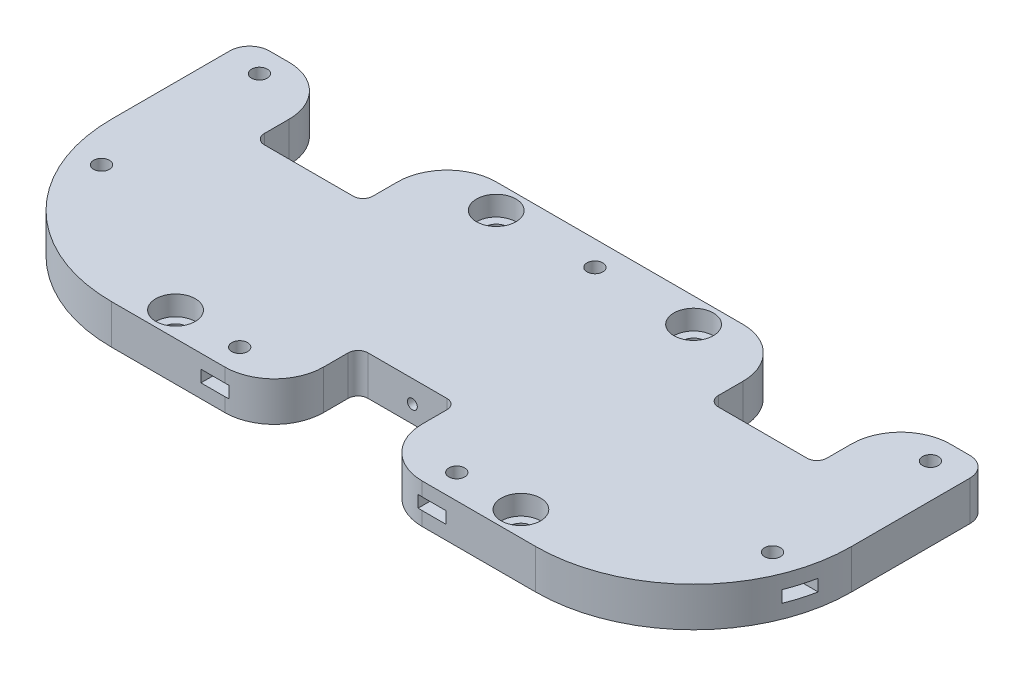
SolidWorks part; units mm, degrees
ref_plane "Front Plane" through (0, 0, 0) normal (0, 0, 1) x (1, 0, 0)
ref_plane "Top Plane" through (0, 0, 0) normal (0, 1, 0) x (1, 0, 0)
ref_plane "Right Plane" through (0, 0, 0) normal (1, 0, 0) x (0, 0, -1)
sketch "Sketch1" plane through (0, 0, 0) normal (0, 1, 0) x (1, 0, 0)
  line L1 (75, -13) -> (-75, -13)
  line L2 (75, -13) -> (75, 13)
  line L3 (75, 13) -> (-75, 13)
  line L4 (-75, -13) -> (-75, 13)
  line L5 (75, -13) -> (-75, 13) construction
  line L6 (75, 13) -> (-75, -13) construction
  point P0 (0, 0)
  dimension "D1" = 26
  dimension "D2" = 150
extrude "Boss-Extrude1" add sketch "Sketch1" along normal blind 8
sketch "Sketch2" plane through (0, 0, -13) normal (0, 0, -1) x (-1, 0, 0)
  line L0 (-75, 0) -> (75, 0) construction
  circle A0 centre (47.4, 3.5) radius 1
  circle A1 centre (-49.4, 3.5) radius 1
  dimension "D1" = 2
  dimension "D2" = 3.5
  dimension "D3" = 47.4
  dimension "D4" = 49.4
extrude "Cut-Extrude1" cut sketch "Sketch2" against normal blind 10
sketch "Sketch3" plane through (0, 0, 13) normal (0, 0, 1) x (1, 0, 0)
  line L0 (-75, 0) -> (75, 0) construction
  circle A0 centre (1, 3.5) radius 1
  dimension "D2" = 2
  dimension "D1" = 1
  dimension "D3" = 3.5
extrude "Cut-Extrude2" cut sketch "Sketch3" against normal blind 10 contours A0
sketch "Sketch4" plane through (0, 0, 0) normal (0, 1, 0) x (1, 0, 0)
  line L0 (-75, 13) -> (-75, -13) construction
  line L1 (-75, 0) -> (-10, 0)
  line L2 (-75, 0) -> (-75, -30)
  line L3 (-75, -30) -> (-10, -30)
  line L4 (-10, 0) -> (-10, -30)
  line L6 (10, 0) -> (75, 0)
  line L7 (10, 0) -> (10, -30)
  line L8 (10, -30) -> (75, -30)
  line L9 (75, 0) -> (75, -30)
  dimension "D1" = 20
  dimension "D2" = 30
extrude "Boss-Extrude2" add sketch "Sketch4" along normal up to surface (8 mm away) up to face at (0, 8, 0)
fillet "Fillet1" radius 32 2 edges at (75, 4, 30) (-75, 4, 30)
sketch "Sketch5" plane through (0, 0, 0) normal (0, 1, 0) x (1, 0, 0)
  line L1 (-35, 0) -> (35, 0)
  line L2 (-35, 0) -> (-35, 30)
  line L3 (-35, 30) -> (35, 30)
  line L4 (35, 0) -> (35, 30)
  dimension "D1" = 70
  dimension "D2" = 30
extrude "Boss-Extrude3" add sketch "Sketch5" along normal up to surface (8 mm away) up to face at (0, 8, 12.9255)
sketch "Sketch6" plane through (0, 0, 0) normal (0, -1, 0) x (1, 0, 0)
  point P0 (35, 25)
  point P1 (-35, 25)
  point P4 (-20, -25)
  point P6 (20, -25)
hole_wizard "CBORE for M4 SHCS1" positions "Sketch9" profile "Sketch8" counterbore size "M4" standard "ANSI Metric" end condition through all
sketch "Sketch9" plane through (0, 8, 0) normal (0, 1, 0) x (1, 0, 0)
  point P0 (-20, 25)
  point P3 (20, 25)
  point P6 (35, -25)
  point P9 (-35, -25)
sketch "Sketch8" plane through (-20, 8, -25) normal (1, 0, 0) x (0, 0, 1)
  line L0 (0, 0) -> (0, 8)
  line L1 (0, 8) -> (2.25, 8)
  line L3 (2.25, 8) -> (2.25, 4)
  line L4 (2.25, 4) -> (4, 4)
  line L5 (4, 4) -> (4, 0)
  line L7 (4, 0) -> (0, 0)
  line L11 (0, -6.35) -> (0, 107.95) construction
  dimension "Thru Hole Dia." = 4.5
  dimension "Thru Hole Depth" = 8
  dimension "C'Bore Dia." = 8
  dimension "C'Bore Depth" = 4
sketch "Sketch10" plane through (0, 8, 0) normal (0, 1, 0) x (1, 0, 0)
  line L0 (35, 30) -> (-35, 30) construction
  line L1 (-75, 13) -> (-57, 13)
  line L2 (-75, 13) -> (-75, 30)
  line L3 (-75, 30) -> (-57, 30)
  line L4 (-57, 13) -> (-57, 30)
  line L5 (75, 13) -> (57, 13)
  line L6 (75, 13) -> (75, 30)
  line L7 (75, 30) -> (57, 30)
  line L8 (57, 13) -> (57, 30)
  dimension "D1" = 18
extrude "Boss-Extrude4" add sketch "Sketch10" against normal up to surface (8 mm away) up to face at (-20, 0, -22.75)
fillet "Fillet2" radius 10 6 edges at (35, 4, -30) (-35, 4, -30) (10, 4, 30) (-10, 4, 30) (57, 4, -30) (-57, 4, -30)
fillet "Fillet3" radius 2 6 edges at (35, 4, -13) (10, 4, 13) (-10, 4, 13) (-35, 4, -13) (-57, 4, -13) (57, 4, -13)
fillet "Fillet4" radius 4 2 edges at (75, 4, -30) (-75, 4, -30)
sketch "Sketch11" plane through (0, 8, 0) normal (0, 1, 0) x (1, 0, 0)
  circle A0 centre (-68, 25) radius 1.6
  circle A1 centre (-68, -7) radius 1.6
  circle A4 centre (0, 25) radius 1.6
  circle A5 centre (-22, -25) radius 1.6
  circle A6 centre (22, -25) radius 1.6
  circle A9 centre (68, -7) radius 1.6
  circle A10 centre (68, 25) radius 1.6
  dimension "D1" = 3.2
extrude "Cut-Extrude3" cut sketch "Sketch11" against normal through all
sketch "Sketch12" plane through (0, 8, 0) normal (0, 1, 0) x (1, 0, 0)
  point P0 (-68, 25)
  point P1 (-68, -7)
  point P5 (-22, -25)
  point P9 (0, 25)
  point P11 (22, -25)
  point P15 (68, -7)
  point P17 (68, 25)
sketch "Sketch14" plane through (0, 8, 0) normal (0, 1, 0) x (1, 0, 0)
  line L0 (19.15, -26.6454) -> (19.15, -29.9638)
  line L1 (19.15, -29.9638) -> (19.15, -31.0884)
  line L2 (19.15, -31.0884) -> (24.85, -31.0884)
  line L3 (-70.85, 26.6454) -> (-70.85, 23.3546)
  line L4 (-70.85, 23.3546) -> (-68, 21.7091)
  line L5 (-68, 21.7091) -> (-65.15, 23.3546)
  line L6 (-65.15, 23.3546) -> (-65.15, 26.6454)
  line L7 (-66.3546, -9.85) -> (-64.7091, -7)
  line L8 (-64.7091, -7) -> (-66.3546, -4.15)
  line L9 (-66.3546, -4.15) -> (-69.6454, -4.15)
  line L10 (24.85, -31.0884) -> (24.85, -30)
  line L12 (-69.6454, -9.85) -> (-66.3546, -9.85)
  line L13 (24.85, -26.6454) -> (24.85, -30)
  line L14 (20, -30) -> (43, -30) construction
  line L17 (69.6454, -4.15) -> (74.8554, -4.15)
  line L19 (-19.15, -26.6454) -> (-19.15, -23.3546)
  line L20 (-19.15, -23.3546) -> (-22, -21.7091)
  line L21 (-22, -21.7091) -> (-24.85, -23.3546)
  line L22 (-24.85, -23.3546) -> (-24.85, -26.6454)
  line L25 (69.6454, -9.85) -> (74.8554, -9.85)
  line L26 (74.8554, -4.15) -> (74.8554, -9.85)
  line L28 (65.15, 26.6454) -> (65.15, 32.1621)
  line L29 (65.15, 32.1621) -> (70.85, 32.1621)
  line L30 (70.85, 26.6454) -> (70.85, 32.1621)
  line L33 (-2.85, 26.6454) -> (-2.85, 23.3546)
  line L34 (-2.85, 23.3546) -> (0, 21.7091)
  line L35 (0, 21.7091) -> (2.85, 23.3546)
  line L36 (2.85, 23.3546) -> (2.85, 26.6454)
  line L38 (-2.85, 26.6454) -> (-2.85, 32.1621)
  line L39 (-2.85, 32.1621) -> (2.85, 32.1621)
  line L40 (2.85, 26.6454) -> (2.85, 32.1621)
  line L42 (-70.85, 26.6454) -> (-70.85, 32.1621)
  line L43 (24.85, -26.6454) -> (24.85, -23.3546)
  line L44 (24.85, -23.3546) -> (22, -21.7091)
  line L45 (22, -21.7091) -> (19.15, -23.3546)
  line L46 (19.15, -23.3546) -> (19.15, -26.6454)
  line L49 (-70.85, 32.1621) -> (-65.15, 32.1621)
  line L50 (-65.15, 26.6454) -> (-65.15, 32.1621)
  line L51 (-69.6454, -4.15) -> (-77.0635, -4.15)
  line L53 (-69.6454, -9.85) -> (-77.0635, -9.85)
  line L54 (-77.0635, -4.15) -> (-77.0635, -9.85)
  line L55 (66.3546, -4.15) -> (64.7091, -7)
  line L56 (64.7091, -7) -> (66.3546, -9.85)
  line L57 (66.3546, -9.85) -> (69.6454, -9.85)
  line L60 (69.6454, -4.15) -> (66.3546, -4.15)
  line L61 (68, 21.7091) -> (70.85, 23.3546)
  line L62 (70.85, 23.3546) -> (70.85, 26.6454)
  line L65 (65.15, 26.6454) -> (65.15, 23.3546)
  line L66 (65.15, 23.3546) -> (68, 21.7091)
  line L68 (-24.85, -26.6454) -> (-24.85, -31.7239)
  line L69 (-24.85, -31.7239) -> (-19.15, -31.7239)
  line L70 (-19.15, -26.6454) -> (-19.15, -31.7239)
  line L71 (-66.575, 27.4682) -> (-68, 28.2909) [skipped]
  line L72 (-68, 28.2909) -> (-69.425, 27.4682) [skipped]
  line L73 (-70.4682, -5.575) -> (-71.2909, -7) [skipped]
  line L74 (-70.4682, -8.425) -> (-69.6454, -9.85) [skipped]
  line L75 (-22, -28.2909) -> (-20.575, -27.4682) [skipped]
  line L76 (-24.85, -26.6454) -> (-23.425, -27.4682) [skipped]
  line L77 (22, -28.2909) -> (23.425, -27.4682) [skipped]
  line L78 (19.15, -26.6454) -> (20.575, -27.4682) [skipped]
  line L79 (70.4682, -8.425) -> (71.2909, -7) [skipped]
  line L80 (70.4682, -5.575) -> (69.6454, -4.15) [skipped]
  line L81 (69.425, 27.4682) -> (68, 28.2909) [skipped]
  line L82 (66.575, 27.4682) -> (65.15, 26.6454) [skipped]
  line L83 (1.425, 27.4682) -> (0, 28.2909) [skipped]
  line L84 (-1.425, 27.4682) -> (-2.85, 26.6454) [skipped]
  arc A1 (-68, -9.85) -> (-68, -4.15) centre (-68, -7) ccw construction
  arc A2 (10, -20) -> (20, -30) centre (20, -20) ccw construction
  arc A3 (-19.15, -25) -> (-24.85, -25) centre (-22, -25) ccw construction
  arc A4 (-70.85, 25) -> (-65.15, 25) centre (-68, 25) ccw construction
  arc A5 (-2.85, 25) -> (2.85, 25) centre (0, 25) ccw construction
  arc A7 (24.85, -25) -> (19.15, -25) centre (22, -25) ccw construction
  arc A9 (68, -4.15) -> (68, -9.85) centre (68, -7) ccw construction
  arc A10 (65.15, 25) -> (70.85, 25) centre (68, 25) ccw construction
extrude "Cut-Extrude5" cut sketch "Sketch14" along normal blind 2.4 from offset 5.2
